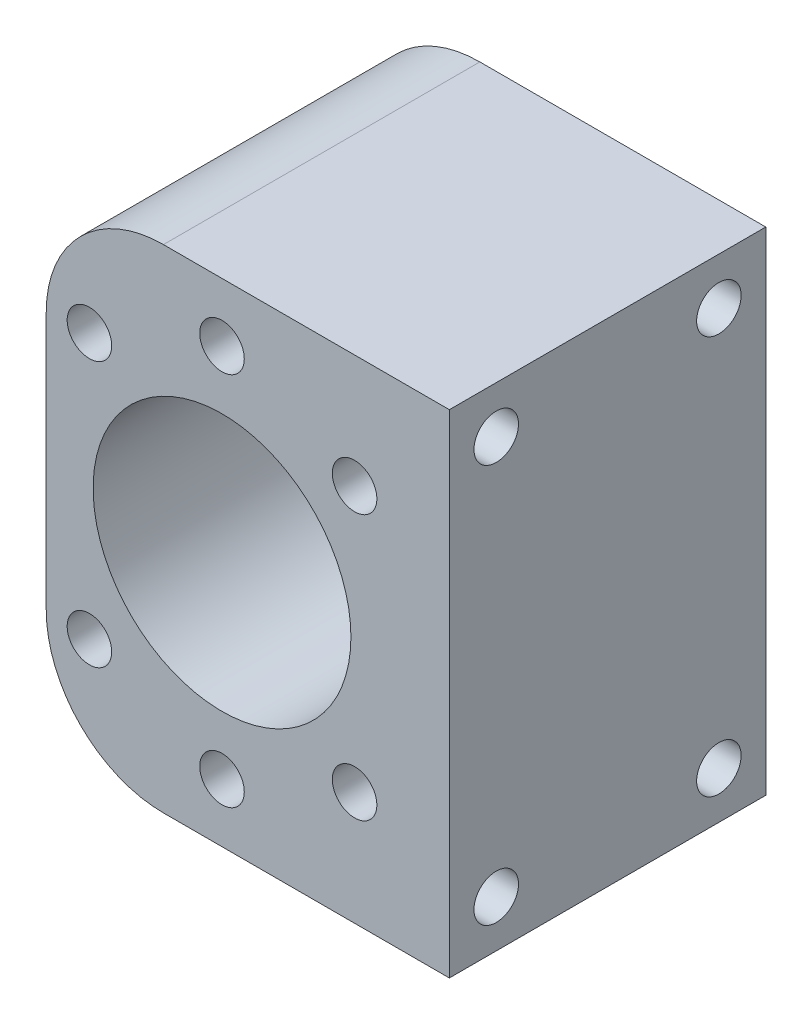
SolidWorks part; units mm, degrees
ref_plane "Front Plane" through (0, 0, 0) normal (0, 0, 1) x (1, 0, 0)
ref_plane "Top Plane" through (0, 0, 0) normal (0, 1, 0) x (1, 0, 0)
ref_plane "Right Plane" through (0, 0, 0) normal (1, 0, 0) x (0, 0, -1)
sketch "Sketch1" plane through (0, 0, 0) normal (0, 0, 1) x (1, 0, 0)
  line L3 (-15, -21) -> (15, -21)
  line L4 (-15, -21) -> (-15, 21)
  line L5 (-15, 21) -> (15, 21)
  line L6 (15, -21) -> (15, 21)
  line L7 (-15, -21) -> (15, 21) construction
  line L8 (-15, 21) -> (15, -21) construction
  dimension "D4" = 30
  dimension "D5" = 42
extrude "Boss-Extrude1" add sketch "Sketch1" along normal mid plane 27
sketch "Sketch2" plane through (0, 0, 13.5) normal (0, 0, 1) x (1, 0, 0)
  circle A0 centre (0, 0) radius 11
  dimension "D1" = 22
extrude "Cut-Extrude1" cut sketch "Sketch2" against normal through all
sketch "Sketch3" plane through (0, 0, 13.5) normal (0, 0, 1) x (1, 0, 0)
  line L0 (0, 21) -> (0, -21) construction
  line L1 (0, 0) -> (-19.8057, 19.8057) construction
  line L2 (0, 0) -> (19.0248, 19.0248) construction
  circle A2 centre (0, 0) radius 16 construction
  circle A3 centre (-11.3137, 11.3137) radius 1.9
  circle A4 centre (0, 16) radius 1.9
  circle A5 centre (11.3137, 11.3137) radius 1.9
  circle A6 centre (11.3137, -11.3137) radius 1.9
  circle A7 centre (0, -16) radius 1.9
  circle A8 centre (-11.3137, -11.3137) radius 1.9
  dimension "D3" = 32
  dimension "D4" = 3.8
  dimension "D5" = 3.8
  dimension "D6" = 3.8
  dimension "D7" = 3.8
  dimension "D8" = 3.8
  dimension "D9" = 3.8
  dimension "D1" = 45
  dimension "D2" = 45
extrude "Cut-Extrude2" cut sketch "Sketch3" against normal blind 10
sketch "Sketch7" plane through (15, 0, 0) normal (1, 0, 0) x (0, 0, -1)
  line L1 (13.5, 21) -> (-13.5, 21)
  line L2 (13.5, 21) -> (13.5, -21)
  line L3 (13.5, -21) -> (-13.5, -21)
  line L4 (-13.5, 21) -> (-13.5, -21)
extrude "Boss-Extrude2" add sketch "Sketch7" along normal blind 4.4
sketch "Sketch6" plane through (19.4, 0, 0) normal (1, 0, 0) x (0, 0, -1)
  line L1 (-9.5, -17) -> (9.5, -17) construction
  line L2 (-9.5, -17) -> (-9.5, 17) construction
  line L3 (-9.5, 17) -> (9.5, 17) construction
  line L4 (9.5, -17) -> (9.5, 17) construction
  line L5 (-9.5, -17) -> (9.5, 17) construction
  line L6 (-9.5, 17) -> (9.5, -17) construction
  circle A0 centre (9.5, 17) radius 1.9
  circle A1 centre (-9.5, 17) radius 1.9
  circle A2 centre (9.5, -17) radius 1.9
  circle A3 centre (-9.5, -17) radius 1.9
  point P12 (0, 0)
  dimension "D1" = 3.8
  dimension "D2" = 3.8
  dimension "D3" = 3.8
  dimension "D4" = 3.8
  dimension "D5" = 34
  dimension "D6" = 19
extrude "Cut-Extrude3" cut sketch "Sketch6" against normal blind 10
fillet "Fillet1" radius 10 2 edges at (-15, -21, 0) (-15, 21, 0)
